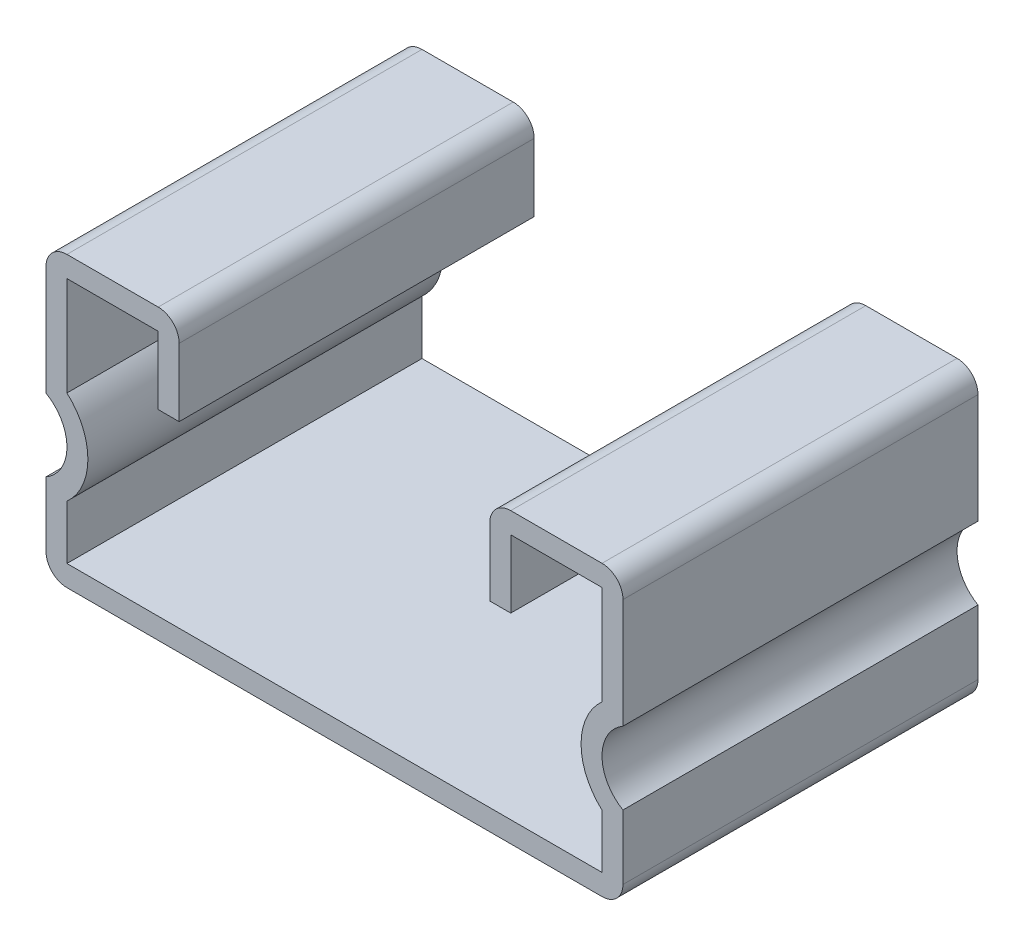
SolidWorks part; units mm, degrees
ref_plane "Plane1" through (0, 0, 0) normal (0, 0, 1) x (1, 0, 0)
ref_plane "Plane2" through (0, 0, 0) normal (0, 1, 0) x (1, 0, 0)
ref_plane "Plane3" through (0, 0, 0) normal (1, 0, 0) x (0, 0, -1)
sketch "Sketch1" plane through (0, 0, 0) normal (0, 0, 1) x (1, 0, 0)
  line L0 (-20.6375, 10.4394) -> (-20.6375, 2.5957)
  line L1 (-20.6375, -2.5957) -> (-20.6375, -7.2136)
  line L2 (-19.1389, -8.7122) -> (19.1389, -8.7122)
  line L3 (20.6375, -7.2136) -> (20.6375, -2.5957)
  line L4 (20.6375, 2.5957) -> (20.6375, 10.4394)
  line L5 (19.1389, 11.938) -> (12.6111, 11.938)
  line L6 (11.1125, 10.4394) -> (11.1125, 5.588)
  line L7 (-19.1389, 11.938) -> (-12.6111, 11.938)
  line L8 (-11.1125, 10.4394) -> (-11.1125, 5.588)
  line L9 (19.1389, -5.2823) -> (19.1389, 6.4389) construction
  line L10 (-19.1389, 6.4389) -> (-19.1389, -5.2823) construction
  line L11 (-12.6111, 10.4394) -> (-12.6111, 5.588)
  line L12 (-19.1389, 10.4394) -> (-12.6111, 10.4394)
  line L13 (-19.1389, 10.4394) -> (-19.1389, 3.351)
  line L14 (-19.1389, -3.351) -> (-19.1389, -7.2136)
  line L15 (-19.1389, -7.2136) -> (19.1389, -7.2136)
  line L16 (19.1389, -7.2136) -> (19.1389, -3.351)
  line L17 (19.1389, 3.351) -> (19.1389, 10.4394)
  line L18 (19.1389, 10.4394) -> (12.6111, 10.4394)
  line L19 (12.6111, 10.4394) -> (12.6111, 5.588)
  line L20 (-12.6111, 5.588) -> (-11.1125, 5.588)
  line L21 (11.1125, 5.588) -> (12.6111, 5.588)
  arc A0 (20.6375, 2.5957) -> (20.6375, -2.5957) centre (22.1361, 0) ccw
  arc A1 (-20.6375, -2.5957) -> (-20.6375, 2.5957) centre (-22.1361, 0) ccw
  arc A2 (-12.6111, 11.938) -> (-11.1125, 10.4394) centre (-12.6111, 10.4394) cw
  arc A3 (-20.6375, 10.4394) -> (-19.1389, 11.938) centre (-19.1389, 10.4394) cw
  arc A4 (-19.1389, -8.7122) -> (-20.6375, -7.2136) centre (-19.1389, -7.2136) cw
  arc A5 (20.6375, -7.2136) -> (19.1389, -8.7122) centre (19.1389, -7.2136) cw
  arc A6 (19.1389, 11.938) -> (20.6375, 10.4394) centre (19.1389, 10.4394) cw
  arc A7 (11.1125, 10.4394) -> (12.6111, 11.938) centre (12.6111, 10.4394) cw
  arc A8 (-19.1389, -3.351) -> (-19.1389, 3.351) centre (-22.1361, 0) ccw
  arc A9 (19.1389, 3.351) -> (19.1389, -3.351) centre (22.1361, 0) ccw
  dimension "D9" = 2.9972
  dimension "D10" = 2.9972
  dimension "D1" = 20.6375
  dimension "Width" = 41.275
  dimension "base" = 8.7122
  dimension "ToeHt" = 11.938
  dimension "D6" = 22.225
  dimension "edge" = 9.525
  dimension "Lip" = 6.35
  dimension "gauge" = 1.4986
extrude "Base-Extrude" add sketch "Sketch1" along normal mid plane 25.4
equation "\"D1@Sketch1\" = \"Width@Sketch1\" / 2"
equation "\"D6@Sketch1\" = \"Width@Sketch1\" - 2 * \"edge@Sketch1\""
equation "\"D10@Sketch1\" = 2 * \"gauge@Sketch1\""
equation "\"D9@Sketch1\" = \"D10@Sketch1\""
